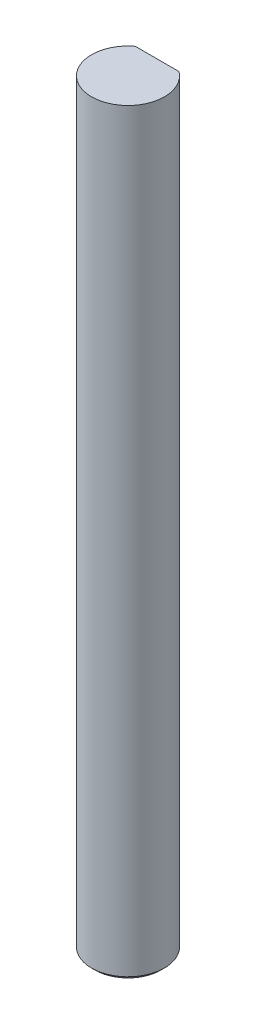
SolidWorks part; units mm, degrees
ref_plane "前视基准面" through (0, 0, 0) normal (0, 0, 1) x (1, 0, 0)
ref_plane "上视基准面" through (0, 0, 0) normal (0, 1, 0) x (1, 0, 0)
ref_plane "右视基准面" through (0, 0, 0) normal (1, 0, 0) x (0, 0, -1)
other "Configuration Table"
sketch "草图1" plane through (0, 0, 0) normal (0, 1, 0) x (1, 0, 0)
  circle A0 centre (0, 0) radius 2.5
  dimension "D1" = 5
extrude "凸台-拉伸1" add sketch "草图1" along normal blind 52
sketch "草图2" plane through (0, 0, 0) normal (0, 1, 0) x (1, 0, 0)
  line L0 (0, 2.5) -> (0, -2.5) construction
  line L1 (-1.5, 2) -> (1.5, 2)
  circle A0 centre (0, 0) radius 2.5 construction
  arc A1 (1.5, 2) -> (-1.5, 2) centre (0, 0) ccw
  point P10 (0, 2)
  dimension "D1" = 5
  dimension "D2" = 4.5
extrude "切除-拉伸1" cut sketch "草图2" against normal blind 15 from surface at 52 starting at face at (0, 52, 2.5)
chamfer "倒角1" distance 0.25 angle 45 1 edges at (0, 0, 2.5)
